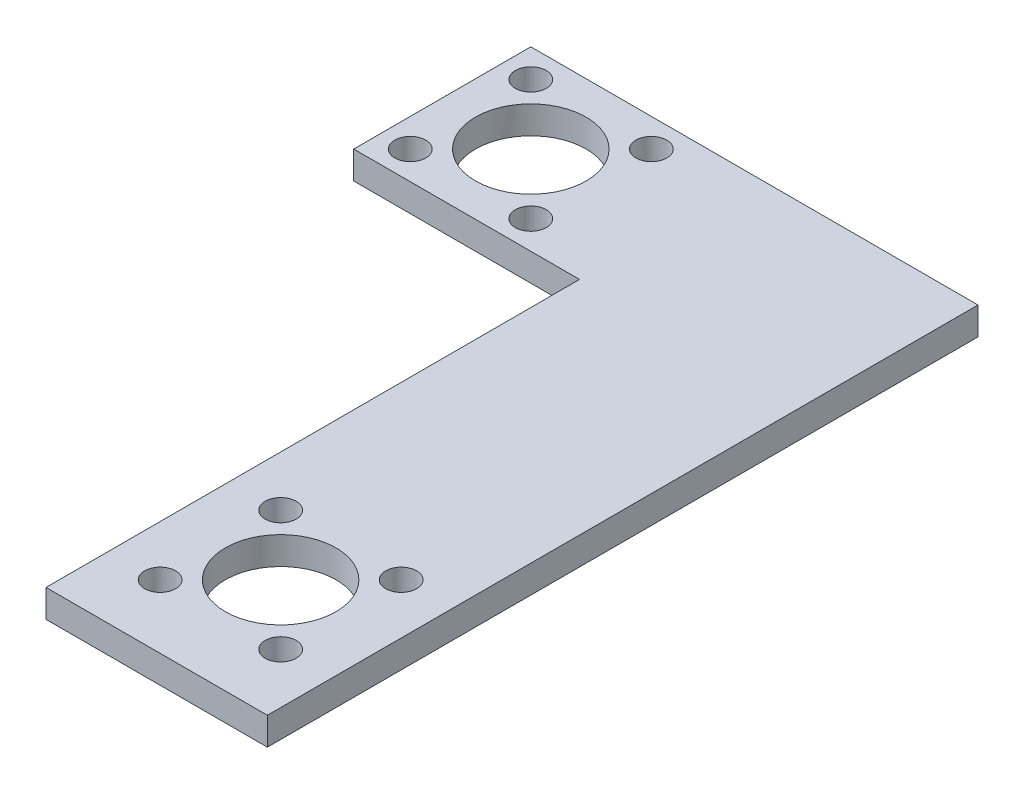
SolidWorks part; units mm, degrees
ref_plane "Front Plane" through (0, 0, 0) normal (0, 0, 1) x (1, 0, 0)
ref_plane "Top Plane" through (0, 0, 0) normal (0, 1, 0) x (1, 0, 0)
ref_plane "Right Plane" through (0, 0, 0) normal (1, 0, 0) x (0, 0, -1)
sketch "Sketch1" plane through (0, 0, 0) normal (0, 1, 0) x (1, 0, 0)
  line L0 (0, 0) -> (-51.308, 0)
  line L1 (0, 0) -> (0, -81.534)
  line L2 (-51.308, 0) -> (-51.308, -20.32)
  line L3 (0, -81.534) -> (-25.4, -81.534)
  line L4 (-25.4, -81.534) -> (-25.4, -20.32)
  line L5 (-51.308, -20.32) -> (-25.4, -20.32)
  dimension "D1" = 20.32
  dimension "D2" = 61.214
  dimension "D3" = 51.308
  dimension "D4" = 25.908
extrude "Boss-Extrude1" add sketch "Sketch1" along normal blind 3.175
sketch "Sketch7" plane through (0, 3.175, 0) normal (0, 1, 0) x (1, 0, 0)
  line L0 (-12.7, -57.15) -> (-12.7, -77.47) construction
  line L2 (-12.7, -57.15) -> (0, -57.15) construction
  line L3 (0, -81.534) -> (0, 0) construction
  line L4 (-12.7, -67.31) -> (-5.7852, -74.2248) construction
  line L5 (-12.7, -67.31) -> (-19.6148, -74.2248) construction
  line L6 (-12.7, -67.31) -> (-19.6148, -60.3952) construction
  line L7 (-12.7, -67.31) -> (-5.7852, -60.3952) construction
  circle A0 centre (-12.7, -67.31) radius 6.35
  circle A1 centre (-5.7852, -60.3952) radius 1.778
  circle A2 centre (-5.7852, -74.2248) radius 1.778
  circle A3 centre (-19.6148, -74.2248) radius 1.778
  circle A4 centre (-19.6148, -60.3952) radius 1.778
extrude "Cut-Extrude3" cut sketch "Sketch7" against normal blind 3.175
sketch "Sketch8" plane through (0, 3.175, 0) normal (0, 1, 0) x (1, 0, 0)
  line L0 (-51.308, -10.16) -> (-30.988, -10.16) construction
  line L1 (-51.308, 0) -> (-51.308, -20.32) construction
  line L2 (-41.148, -10.16) -> (-34.2332, -3.2452) construction
  line L3 (-41.148, -10.16) -> (-48.0628, -3.2452) construction
  line L4 (-41.148, -10.16) -> (-34.2332, -17.0748) construction
  line L5 (-41.148, -10.16) -> (-48.0628, -17.0748) construction
  circle A0 centre (-41.148, -10.16) radius 6.35
  circle A1 centre (-48.0628, -3.2452) radius 1.778
  circle A2 centre (-34.2332, -3.2452) radius 1.778
  circle A3 centre (-34.2332, -17.0748) radius 1.778
  circle A4 centre (-48.0628, -17.0748) radius 1.778
extrude "Cut-Extrude4" cut sketch "Sketch8" against normal up to next
